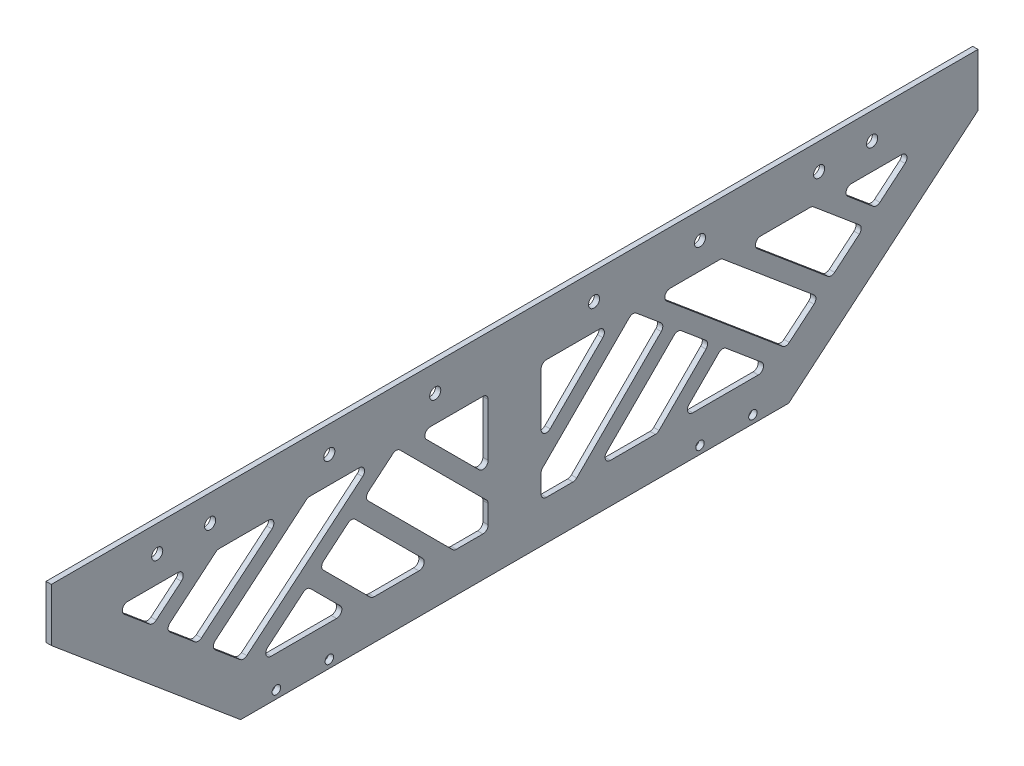
SolidWorks part; units mm, degrees
material "环氧树脂FR-4"
ref_plane "前视基准面" through (0, 0, 0) normal (0, 0, 1) x (1, 0, 0)
ref_plane "上视基准面" through (0, 0, 0) normal (0, 1, 0) x (1, 0, 0)
ref_plane "右视基准面" through (0, 0, 0) normal (1, 0, 0) x (0, 0, -1)
sketch "草图1" plane through (0, 0, 0) normal (1, 0, 0) x (0, 0, -1)
  line L0 (-103.4948, -80) -> (103.4948, -80)
  line L1 (-175, 0) -> (175, 0)
  line L2 (-175, 0) -> (-175, -20)
  line L4 (175, 0) -> (175, -20)
  line L5 (103.4948, -80) -> (175, -20)
  line L6 (-103.4948, -80) -> (-175, -20)
  dimension "D1" = 0
  dimension "D2" = 350
  dimension "D3" = 175
  dimension "D4" = 20
  dimension "D6" = 140
  dimension "D7" = 140
  dimension "90" = 80
  dimension "D8" = 350
extrude "凸台-拉伸1" add sketch "草图1" along normal blind 2
sketch "草图2" plane through (2, 0, 0) normal (1, 0, 0) x (0, 0, -1)
  line L0 (-103.4948, -80) -> (103.4948, -80) construction
  line L1 (0, 55) -> (0, -55) construction
  point P0 (-70, -77)
  point P4 (-90, -77)
  point P7 (90, -77)
  point P8 (70, -77)
  dimension "D1" = 70
  dimension "D2" = 3
  dimension "D4" = 20
  dimension "D3" = 2
hole_wizard "Ø3.2 (3.2) 直径孔1" positions "3D草图1" profile "草图3" hole size "Ø3.2" standard "GB" end condition through all
sketch3d "3D草图1"
  point P0 (2, -77, 90)
  point P3 (2, -77, 70)
  point P6 (2, -77, -90)
  point P9 (2, -77, -70)
sketch "草图3" plane through (2, -77, 90) normal (0, 1, 0) x (0, 0, -1)
  line L0 (0, 0) -> (0, 2)
  line L1 (0, 2) -> (1.6, 2)
  line L2 (1.6, 2) -> (1.6, 0)
  line L5 (1.6, 0) -> (0, 0)
  line L11 (0, -6.35) -> (0, 107.95) construction
  dimension "通孔孔直径" = 3.2
  dimension "通孔孔深度" = 2
sketch "草图4" plane through (2, 0, 0) normal (1, 0, 0) x (0, 0, -1)
  line L0 (175, 0) -> (-175, 0) construction
  line L1 (-175, 0) -> (-175, -20) construction
  point P0 (-30, -10)
  point P4 (-70, -10)
  point P5 (-135, -10)
  point P10 (-115, -10)
  dimension "D1" = 30
  dimension "D2" = 10
  dimension "D4" = 40
  dimension "D5" = 40
  dimension "D6" = 10
  dimension "D8" = 20
  dimension "D3" = 2
  dimension "D7" = 2
hole_wizard "Ø4.2 (4.2) 直径孔1" positions "3D草图2" profile "草图5" hole size "Ø4.2" standard "GB" end condition through all
sketch3d "3D草图2"
  point P0 (2, -10, 135)
  point P3 (2, -10, 115)
  point P6 (2, -10, 70)
  point P9 (2, -10, 30)
sketch "草图5" plane through (2, -10, 135) normal (0, 1, 0) x (0, 0, -1)
  line L0 (0, 0) -> (0, 2)
  line L1 (0, 2) -> (2.1, 2)
  line L2 (2.1, 2) -> (2.1, 0)
  line L5 (2.1, 0) -> (0, 0)
  line L11 (0, -6.35) -> (0, 107.95) construction
  dimension "通孔孔直径" = 4.2
  dimension "通孔孔深度" = 2
mirror "镜向1" about plane through (0, 0, 0) normal (0, 0, 1) of "Ø4.2 (4.2) 直径孔1"
sketch "草图6" plane through (2, 0, 0) normal (1, 0, 0) x (0, 0, -1)
  line L23 (-87.4382, -20) -> (-119.5512, -46.946)
  line L24 (-78.1039, -20) -> (-114.884, -50.8622)
  line L44 (-78.1039, -20) -> (-53.2123, -20)
  line L63 (-119.5512, -46.946) -> (-131.997, -36.5027)
  line L67 (-53.2123, -20) -> (-102.4382, -61.3055)
  line L68 (-44.6041, -20.6093) -> (-56.9076, -30.9332)
  line L69 (-151.6641, -20) -> (-121.6641, -20)
  line L70 (-10, -20) -> (-10, -46.7281)
  line L71 (-10, -65) -> (-22.8408, -65)
  line L72 (-102.4382, -61.3055) -> (-114.884, -50.8622)
  line L73 (-175, -20) -> (-103.4948, -80) construction
  line L74 (175, 0) -> (-175, 0) construction
  line L75 (-103.4948, -80) -> (103.4948, -80) construction
  line L76 (-36.7281, -20) -> (-10, -20)
  line L77 (-121.6641, -20) -> (-136.6641, -32.5865)
  line L78 (-112.3298, -20) -> (-131.997, -36.5027)
  line L79 (-112.3298, -20) -> (-87.4382, -20)
  line L80 (-31.3261, -65) -> (-53.9535, -65)
  line L81 (-136.6641, -32.5865) -> (-151.6641, -20)
  line L82 (-78.4388, -49) -> (-62.4388, -65)
  line L83 (-61.5215, -34.8047) -> (-31.3261, -65)
  line L84 (-56.9076, -30.9332) -> (-22.8408, -65)
  line L85 (-44.6041, -20.6093) -> (-10, -55.2134)
  line L86 (-36.7281, -20) -> (-10, -46.7281)
  line L87 (-62.4388, -65) -> (-97.5069, -65)
  line L88 (-78.4388, -49) -> (-97.5069, -65)
  line L89 (-73.825, -45.1285) -> (-53.9535, -65)
  line L90 (-64.4835, -23.3573) -> (-12.9904, -74.8504) construction
  line L91 (-61.5215, -34.8047) -> (-73.825, -45.1285)
  line L92 (-10, -55.2134) -> (-10, -65)
  line L93 (-53.1698, -12.0436) -> (-1.6767, -63.5367) construction
  line L94 (-48.9272, -7.801) -> (2.5659, -59.2941) construction
  point P3 (-97.8205, -20)
  point P4 (-88.0352, -65)
  point P9 (-7.5, -20)
  point P13 (-105.7293, -10.4978)
  point P14 (-142.9441, -54.8486)
  point P15 (-101.8655, -16.7861)
  point P16 (-124.6851, -51.7601)
  point P17 (-128.5154, -48.5462)
  point P18 (-85.5963, -69.3648)
  point P19 (-108.0274, -8.5694)
  point P20 (-5.0611, -24.3648)
  point P21 (-90.4741, -60.6352)
  point P22 (-9.9389, -15.6352)
  point P23 (-145.2422, -52.9202)
  point P24 (-103.4312, -12.4261)
  point P25 (-140.6459, -56.777)
  dimension "D1" = 20
  dimension "D2" = 15
  dimension "D3" = 10
  dimension "D4" = 15
  dimension "D5" = 30
  dimension "D6" = 15
  dimension "D7" = 6
  dimension "D8" = 16
  dimension "D9" = 6
  dimension "D10" = 16
  dimension "D11" = 6
  dimension "D12" = 16
  dimension "D13" = 16
  dimension "D14" = 6
  dimension "D15" = 16
  dimension "D16" = 6
  dimension "D17" = 16
  dimension "D18" = 6
extrude "切除-拉伸1" cut sketch "草图6" against normal through all
fillet "圆角1" radius 2 26 edges at (1, -20, 36.7281) (1, -20, 10) (1, -46.7281, 10) (1, -55.2134, 10) (1, -65, 22.8408) (1, -65, 10) (1, -30.9332, 56.9076) (1, -20.6093, 44.6041) (1, -34.8047, 61.5215) (1, -65, 31.3261) (1, -65, 53.9535) (1, -45.1285, 73.825) (1, -65, 62.4388) (1, -49, 78.4388) (1, -65, 97.5069) (1, -20, 53.2123) (1, -20, 78.1039) (1, -61.3055, 102.4382) (1, -50.8622, 114.884) (1, -20, 87.4382) (1, -20, 112.3298) (1, -46.946, 119.5512) (1, -36.5027, 131.997) (1, -32.5865, 136.6641) (1, -20, 121.6641) (1, -20, 151.6641)
mirror "镜向2" about plane through (0, 0, 0) normal (0, 0, 1) of "圆角1", "切除-拉伸1"
